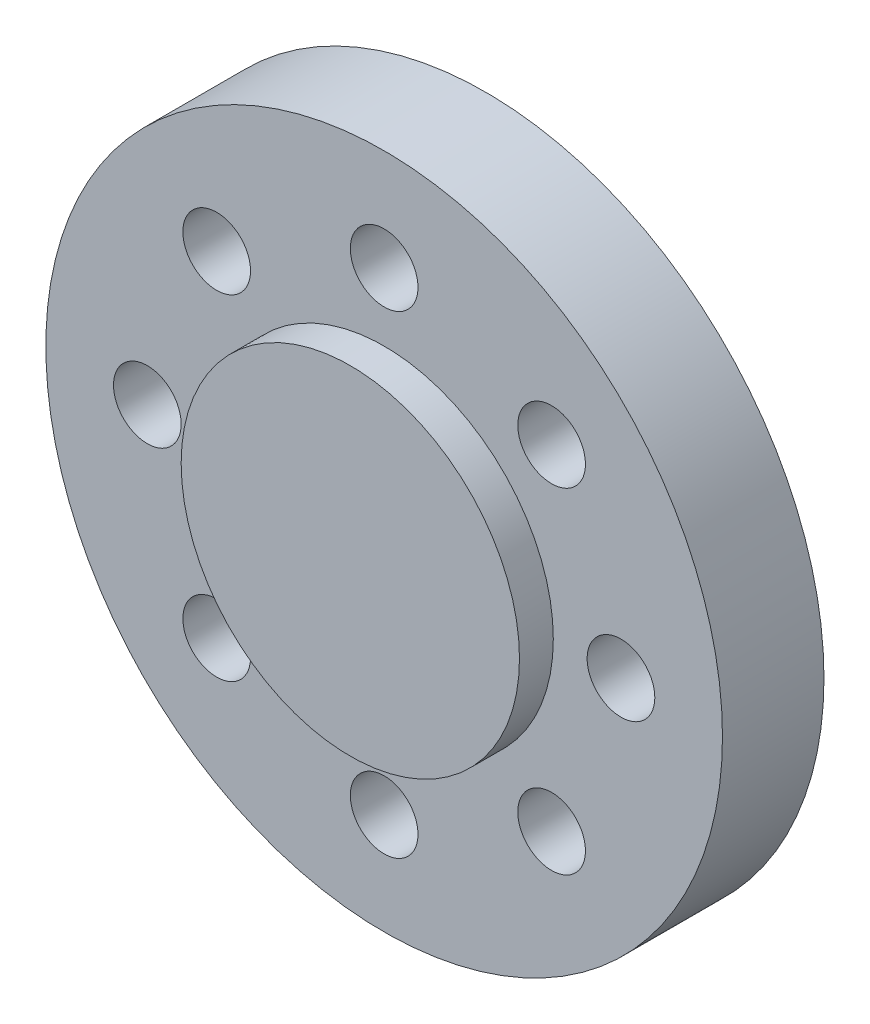
SolidWorks part; units mm, degrees
ref_plane "正面" through (0, 0, 0) normal (0, 0, 1) x (1, 0, 0)
ref_plane "平面" through (0, 0, 0) normal (0, 1, 0) x (1, 0, 0)
ref_plane "右側面" through (0, 0, 0) normal (1, 0, 0) x (0, 0, -1)
sketch "ｽｹｯﾁ1" plane through (0, 0, 0) normal (0, 0, 1) x (1, 0, 0)
  line L0 (4.0171, 4.8456) -> (4.0171, -27.1544) construction
  line L1 (-17.4829, 4.8456) -> (13.5171, 4.8456)
  line L2 (-17.4829, 4.8456) -> (-17.4829, -27.1544)
  line L3 (-17.4829, -27.1544) -> (13.5171, -27.1544)
  line L4 (25.5171, -0.5714) -> (25.5171, -21.7374)
  line L5 (-17.4829, -11.1544) -> (26.5171, -11.1544) construction
  arc A0 (13.5171, -27.1544) -> (25.5171, -21.7374) centre (13.5171, -11.1544) ccw
  arc A1 (25.5171, -0.5714) -> (13.5171, 4.8456) centre (13.5171, -11.1544) ccw
  circle A2 centre (-14.4829, -24.6544) radius 1
  circle A3 centre (12.5171, -24.6544) radius 1
  circle A4 centre (12.5171, 2.3456) radius 1
  circle A5 centre (-14.4829, 2.3456) radius 1
  dimension "D3" = 32
  dimension "D1" = 2
  dimension "D10" = 27
  dimension "D2" = 32
  dimension "D4" = 9.5
  dimension "D5" = 3
  dimension "D6" = 13.5
  dimension "D9" = 13.5
  dimension "D11" = 8.5
  dimension "D12" = 43
  dimension "D13" = 21.5
  dimension "D7" = 2
  dimension "D8" = 2
extrude "ﾎﾞｽ - 押し出し1" add sketch "ｽｹｯﾁ1" along normal blind 32.5
sketch "ｽｹｯﾁ2" plane through (0, 0, 32.5) normal (0, 0, 1) x (1, 0, 0)
  line L0 (-17.4829, 4.8456) -> (-17.4829, -27.1544) construction
  circle A0 centre (13.5171, -11.1544) radius 3
  dimension "D2" = 6
  dimension "D1" = 31
extrude "ﾎﾞｽ - 押し出し2" add sketch "ｽｹｯﾁ2" along normal blind 3.5
sketch "ｽｹｯﾁ3" plane through (0, 0, 36) normal (0, 0, 1) x (1, 0, 0)
  circle A0 centre (13.5171, -11.1544) radius 10
  dimension "D1" = 20
extrude "ﾎﾞｽ - 押し出し3" add sketch "ｽｹｯﾁ3" against normal blind 3
sketch "ｽｹｯﾁ4" plane through (0, 0, 36) normal (0, 0, 1) x (1, 0, 0)
  circle A0 centre (13.5171, -11.1544) radius 5
  dimension "D1" = 10
extrude "ﾎﾞｽ - 押し出し4" add sketch "ｽｹｯﾁ4" along normal blind 1
sketch "ｽｹｯﾁ5" plane through (0, 0, 36) normal (0, 0, 1) x (1, 0, 0)
  circle A0 centre (20.5171, -11.1544) radius 1
  circle A1 centre (13.5171, -11.1544) radius 5 construction
  circle A2 centre (18.4668, -16.1042) radius 1
  circle A3 centre (13.5171, -18.1544) radius 1
  circle A4 centre (8.5673, -16.1042) radius 1
  circle A5 centre (6.5171, -11.1544) radius 1
  circle A6 centre (8.5673, -6.2047) radius 1
  circle A7 centre (13.5171, -4.1544) radius 1
  circle A8 centre (18.4668, -6.2047) radius 1
  point P21 (13.5171, -11.1544)
  dimension "D1" = 2
  dimension "D2" = 7
  dimension "D3" = 8
extrude "ｶｯﾄ - 押し出し1" cut sketch "ｽｹｯﾁ5" against normal blind 3
sketch "ｽｹｯﾁ6" plane through (0, 0, 0) normal (0, 0, -1) x (-1, 0, 0)
  line L1 (17.4829, -27.1544) -> (-34.5957, -27.1544)
  line L2 (17.4829, -27.1544) -> (17.4829, 11.9426)
  line L3 (17.4829, 11.9426) -> (-34.5957, 11.9426)
  line L4 (-34.5957, -27.1544) -> (-34.5957, 11.9426)
extrude "ｶｯﾄ - 押し出し2" cut sketch "ｽｹｯﾁ6" against normal blind 32.5
